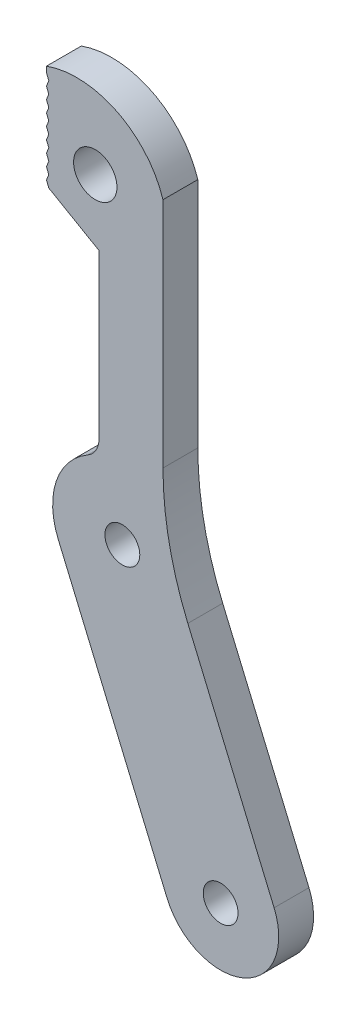
SolidWorks part; units mm, degrees
ref_plane "Front Plane" through (0, 0, 0) normal (0, 0, 1) x (1, 0, 0)
ref_plane "Top Plane" through (0, 0, 0) normal (0, 1, 0) x (1, 0, 0)
ref_plane "Right Plane" through (0, 0, 0) normal (1, 0, 0) x (0, 0, -1)
sketch "Sketch1" plane through (0, 0, 0) normal (0, 0, 1) x (1, 0, 0)
  line L0 (19.9553, -21.6867) -> (19.9553, -7.6867)
  line L1 (19.9553, -7.6867) -> (15.6252, -5.1867)
  line L2 (15.4252, -4.6867) -> (15.6252, -5.1867)
  line L3 (15.4252, -4.6867) -> (15.6252, -4.1867)
  line L4 (16.4357, -30.9581) -> (25.8159, -53.0491)
  line L5 (35.0205, -49.1407) -> (27.5945, -31.652)
  line L6 (25.4553, -21.1407) -> (25.4553, -1.1407)
  line L7 (15.4252, 3.3133) -> (15.4252, 3.8022)
  line L8 (15.4252, -3.6867) -> (15.6252, -4.1867)
  line L9 (15.4252, -3.6867) -> (15.6252, -3.1867)
  line L10 (15.4252, -2.6867) -> (15.6252, -3.1867)
  line L11 (15.4252, -2.6867) -> (15.6252, -2.1867)
  line L12 (15.4252, -1.6867) -> (15.6252, -2.1867)
  line L13 (15.4252, -1.6867) -> (15.6252, -1.1867)
  line L14 (15.4252, -0.6867) -> (15.6252, -1.1867)
  line L15 (15.4252, -0.6867) -> (15.6252, -0.1867)
  line L16 (15.4252, 0.3133) -> (15.6252, -0.1867)
  line L17 (15.4252, 0.3133) -> (15.6252, 0.8133)
  line L18 (15.4252, 1.3133) -> (15.6252, 0.8133)
  line L19 (15.4252, 1.3133) -> (15.6252, 1.8133)
  line L20 (15.4252, 2.3133) -> (15.6252, 1.8133)
  line L21 (15.4252, 2.3133) -> (15.6252, 2.8133)
  line L22 (15.4252, 3.3133) -> (15.6252, 2.8133)
  line L24 (15.4252, 3.3133) -> (15.6252, 3.8133) [skipped]
  arc A0 (19.9553, -21.6867) -> (18.9561, -23.4182) centre (17.9553, -21.6867) cw
  arc A1 (18.9561, -23.4182) -> (16.4357, -30.9581) centre (21.9585, -28.613) ccw
  arc A2 (25.8159, -53.0491) -> (35.0205, -49.1407) centre (30.4182, -51.0949) ccw
  arc A3 (27.5945, -31.652) -> (25.4553, -21.1407) centre (52.3494, -21.1407) cw
  arc A4 (15.4252, 3.8022) -> (25.4553, -1.1407) centre (18.0464, -3.527) cw
  circle A5 centre (30.4182, -51.0949) radius 1.5
  circle A6 centre (19.6252, -2.1867) radius 1.8668
  circle A7 centre (21.9585, -28.613) radius 1.5
  dimension "D1" = 14
  dimension "D3" = 2
  dimension "D4" = 6
  dimension "D6" = 24
  dimension "D8" = 48
  dimension "D10" = 26.8941
  dimension "D14" = 1
  dimension "D16" = 3
  dimension "D17" = 4
  dimension "D18" = 3
  dimension "D2" = 5.5
  dimension "D5" = 10
  dimension "D7" = 20
  dimension "D9" = 19
  dimension "D11" = 5
  dimension "D12" = 0.5385
  dimension "D13" = 120
  dimension "D15" = 9
extrude "Boss-Extrude2" add sketch "Sketch1" along normal blind 3
